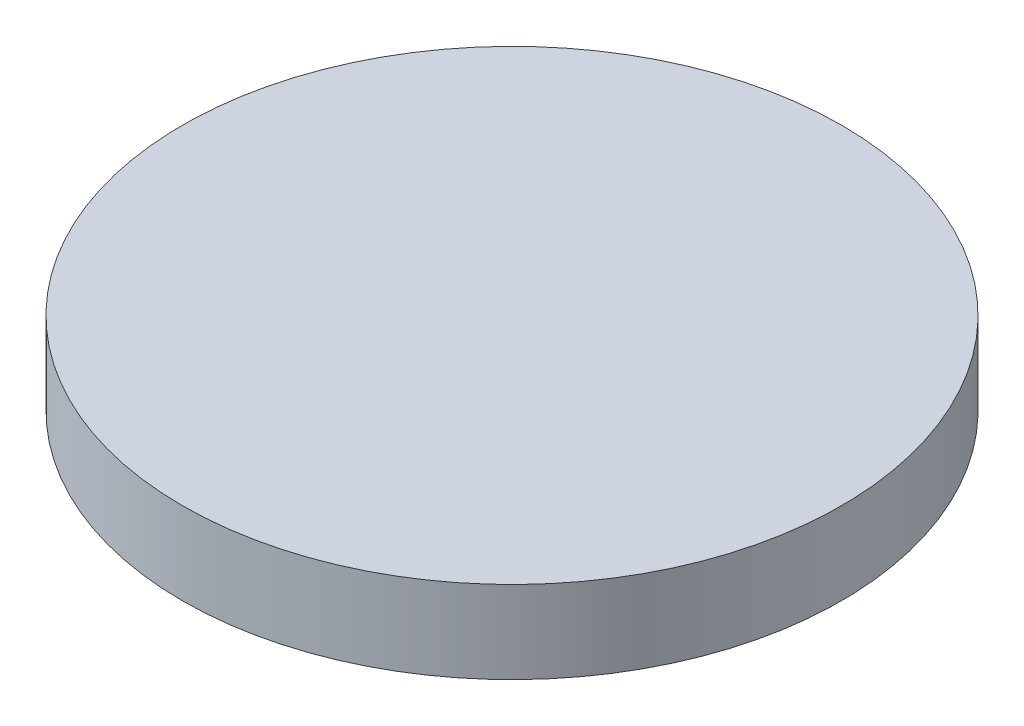
SolidWorks part; units mm, degrees
material "Commercialement pur CP-Ti UNS R50400 (SS)"
ref_plane "Plan de face" through (0, 0, 0) normal (0, 0, 1) x (1, 0, 0)
ref_plane "Plan de dessus" through (0, 0, 0) normal (0, 1, 0) x (1, 0, 0)
ref_plane "Plan de droite" through (0, 0, 0) normal (1, 0, 0) x (0, 0, -1)
sketch "Esquisse1" plane through (0, 0, 0) normal (0, 1, 0) x (1, 0, 0)
  circle A0 centre (0, 0) radius 400
  dimension "D1" = 800
extrude "Boss.-Extru.1" add sketch "Esquisse1" along normal blind 100
